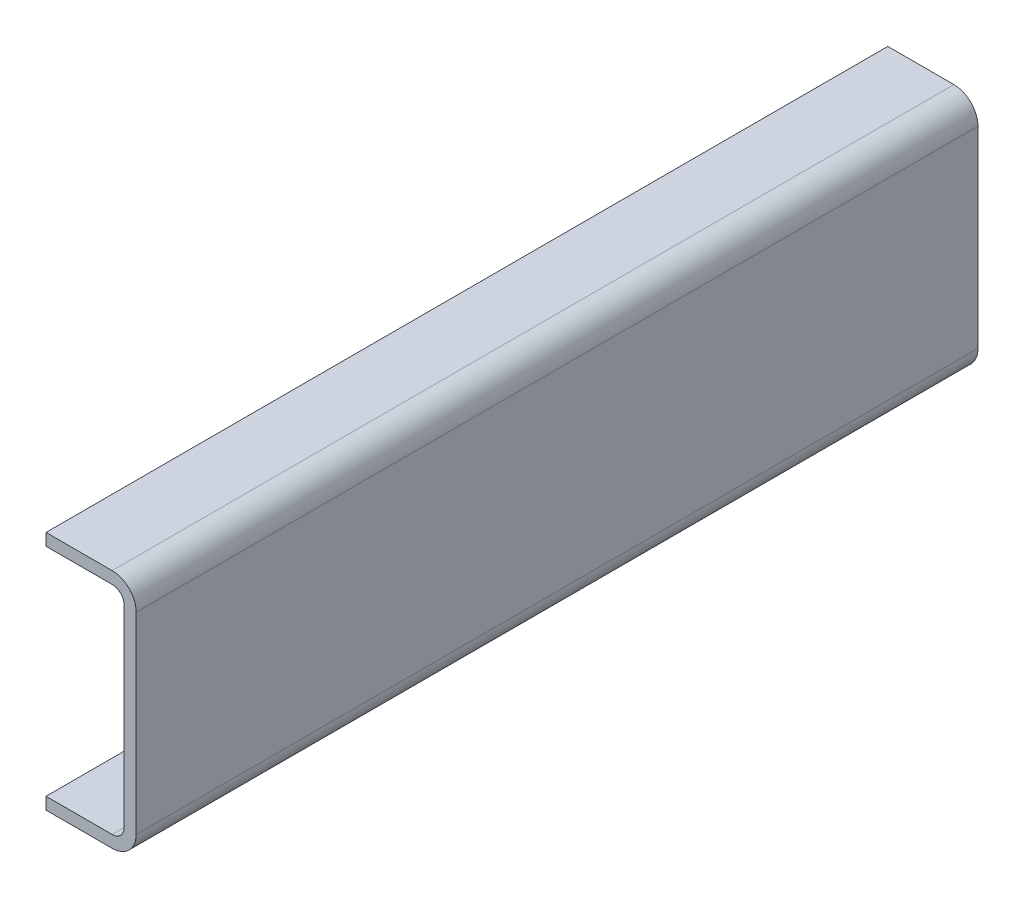
SolidWorks part; units mm, degrees
ref_plane "Front Plane" through (0, 0, 0) normal (0, 0, 1) x (1, 0, 0)
ref_plane "Top Plane" through (0, 0, 0) normal (0, 1, 0) x (1, 0, 0)
ref_plane "Right Plane" through (0, 0, 0) normal (1, 0, 0) x (0, 0, -1)
sketch "Sketch1" plane through (0, 0, 0) normal (0, 0, 1) x (1, 0, 0)
  line L0 (0, 2.54) -> (0, 22.86)
  line L1 (-2.54, 25.4) -> (-9.525, 25.4)
  line L2 (-2.54, 0) -> (-9.525, 0)
  line L3 (-2.54, 1.27) -> (-9.525, 1.27)
  line L4 (-1.27, 2.54) -> (-1.27, 22.86)
  line L5 (-2.54, 24.13) -> (-9.525, 24.13)
  line L6 (-9.525, 25.4) -> (-9.525, 24.13)
  line L7 (-9.525, 1.27) -> (-9.525, 0)
  arc A0 (0, 2.54) -> (-2.54, 0) centre (-2.54, 2.54) cw
  arc A1 (0, 22.86) -> (-2.54, 25.4) centre (-2.54, 22.86) ccw
  arc A2 (-1.27, 2.54) -> (-2.54, 1.27) centre (-2.54, 2.54) cw
  arc A3 (-1.27, 22.86) -> (-2.54, 24.13) centre (-2.54, 22.86) ccw
  point P7 (0, 0)
  point P10 (0, 25.4)
  dimension "D3" = 2.54
  dimension "D1" = 9.525
  dimension "D2" = 25.4
  dimension "D4" = 1.27
extrude "Boss-Extrude1" add sketch "Sketch1" along normal blind 88.9
